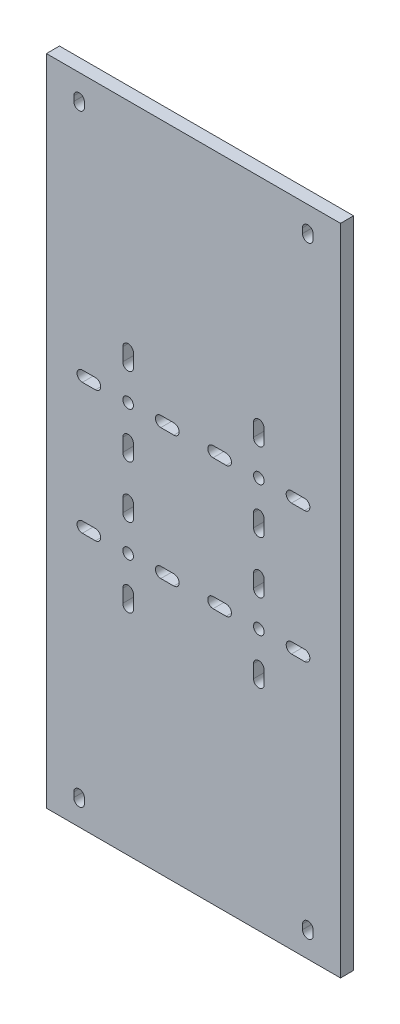
SolidWorks part; units mm, degrees
material "ABS PC"
ref_plane "前视基准面" through (0, 0, 0) normal (0, 0, 1) x (1, 0, 0)
ref_plane "上视基准面" through (0, 0, 0) normal (0, 1, 0) x (1, 0, 0)
ref_plane "右视基准面" through (0, 0, 0) normal (1, 0, 0) x (0, 0, -1)
sketch "草图1" plane through (0, 0, 0) normal (0, 0, 1) x (1, 0, 0)
  line L0 (-90, 369) -> (90, 369)
  line L1 (90, 369) -> (90, -15)
  line L2 (90, -15) -> (-90, -15)
  line L3 (-90, -15) -> (-90, 369)
  line L5 (-70, 360) -> (-70, 363) construction
  line L6 (-73.25, 360) -> (-73.25, 363)
  line L7 (-66.75, 360) -> (-66.75, 363)
  line L8 (0, 398.6227) -> (0, -66.7507) construction
  line L11 (-187.8062, 177) -> (345.6862, 177) construction
  line L12 (70, 360) -> (70, 363) construction
  line L13 (73.25, 360) -> (73.25, 363)
  line L14 (66.75, 360) -> (66.75, 363)
  line L15 (-70, -6) -> (-70, -9) construction
  line L16 (-73.25, -6) -> (-73.25, -9)
  line L17 (-66.75, -6) -> (-66.75, -9)
  line L18 (70, -6) -> (70, -9) construction
  line L19 (73.25, -6) -> (73.25, -9)
  line L20 (66.75, -6) -> (66.75, -9)
  line L21 (40, 217) -> (2, 217) construction
  line L22 (50, 207) -> (30, 207) construction
  line L23 (50, 207) -> (50, 227) construction
  line L24 (50, 227) -> (30, 227) construction
  line L25 (30, 207) -> (30, 227) construction
  line L26 (50, 207) -> (30, 227) construction
  line L27 (50, 227) -> (30, 207) construction
  line L28 (30, 227) -> (2, 227) construction
  line L29 (2, 227) -> (2, 207) construction
  line L30 (2, 207) -> (30, 207) construction
  line L31 (12, 217) -> (20, 217) construction
  line L32 (12, 220.25) -> (20, 220.25)
  line L33 (12, 213.75) -> (20, 213.75)
  line L34 (40, 245) -> (40, 237) construction
  line L37 (43.25, 245) -> (43.25, 237)
  line L40 (36.75, 245) -> (36.75, 237)
  line L43 (-40, 245) -> (-40, 237) construction
  line L46 (-43.25, 245) -> (-43.25, 237)
  line L49 (-36.75, 245) -> (-36.75, 237)
  line L52 (-12, 217) -> (-20, 217) construction
  line L55 (-12, 220.25) -> (-20, 220.25)
  line L58 (-12, 213.75) -> (-20, 213.75)
  line L61 (-40, 189) -> (-40, 197) construction
  line L64 (-36.75, 189) -> (-36.75, 197)
  line L67 (-43.25, 189) -> (-43.25, 197)
  line L70 (-68, 217) -> (-60, 217) construction
  line L73 (-68, 213.75) -> (-60, 213.75)
  line L76 (-68, 220.25) -> (-60, 220.25)
  line L79 (68, 217) -> (60, 217) construction
  line L80 (68, 213.75) -> (60, 213.75)
  line L81 (68, 220.25) -> (60, 220.25)
  line L82 (40, 189) -> (40, 197) construction
  line L83 (36.75, 189) -> (36.75, 197)
  line L84 (43.25, 189) -> (43.25, 197)
  line L85 (-68, 137) -> (-60, 137) construction
  line L86 (-68, 140.25) -> (-60, 140.25)
  line L87 (-68, 133.75) -> (-60, 133.75)
  line L88 (-40, 109) -> (-40, 117) construction
  line L89 (-43.25, 109) -> (-43.25, 117)
  line L90 (-36.75, 109) -> (-36.75, 117)
  line L91 (-12, 137) -> (-20, 137) construction
  line L92 (-12, 133.75) -> (-20, 133.75)
  line L93 (-12, 140.25) -> (-20, 140.25)
  line L94 (-40, 165) -> (-40, 157) construction
  line L95 (-36.75, 165) -> (-36.75, 157)
  line L96 (-43.25, 165) -> (-43.25, 157)
  line L97 (40, 109) -> (40, 117) construction
  line L98 (43.25, 109) -> (43.25, 117)
  line L99 (36.75, 109) -> (36.75, 117)
  line L100 (12, 137) -> (20, 137) construction
  line L101 (12, 133.75) -> (20, 133.75)
  line L102 (12, 140.25) -> (20, 140.25)
  line L103 (68, 137) -> (60, 137) construction
  line L104 (68, 140.25) -> (60, 140.25)
  line L105 (68, 133.75) -> (60, 133.75)
  line L106 (40, 165) -> (40, 157) construction
  line L107 (36.75, 165) -> (36.75, 157)
  line L108 (43.25, 165) -> (43.25, 157)
  arc A0 (-73.25, 360) -> (-66.75, 360) centre (-70, 360) ccw
  arc A1 (-66.75, 363) -> (-73.25, 363) centre (-70, 363) ccw
  arc A4 (73.25, 360) -> (66.75, 360) centre (70, 360) cw
  arc A5 (66.75, 363) -> (73.25, 363) centre (70, 363) cw
  arc A6 (-73.25, -6) -> (-66.75, -6) centre (-70, -6) cw
  arc A7 (-66.75, -9) -> (-73.25, -9) centre (-70, -9) cw
  arc A8 (73.25, -6) -> (66.75, -6) centre (70, -6) ccw
  arc A9 (66.75, -9) -> (73.25, -9) centre (70, -9) ccw
  circle A10 centre (40, 217) radius 3.25
  circle A11 centre (-40, 217) radius 3.25
  circle A12 centre (40, 137) radius 3.25
  circle A13 centre (-40, 137) radius 3.25
  arc A14 (12, 220.25) -> (12, 213.75) centre (12, 217) ccw
  arc A15 (20, 213.75) -> (20, 220.25) centre (20, 217) ccw
  arc A46 (43.25, 245) -> (36.75, 245) centre (40, 245) ccw
  arc A47 (36.75, 237) -> (43.25, 237) centre (40, 237) ccw
  arc A48 (68, 213.75) -> (68, 220.25) centre (68, 217) ccw
  arc A49 (60, 220.25) -> (60, 213.75) centre (60, 217) ccw
  arc A50 (36.75, 189) -> (43.25, 189) centre (40, 189) ccw
  arc A51 (43.25, 197) -> (36.75, 197) centre (40, 197) ccw
  arc A52 (-43.25, 245) -> (-36.75, 245) centre (-40, 245) cw
  arc A53 (-36.75, 237) -> (-43.25, 237) centre (-40, 237) cw
  arc A54 (-12, 220.25) -> (-12, 213.75) centre (-12, 217) cw
  arc A55 (-20, 213.75) -> (-20, 220.25) centre (-20, 217) cw
  arc A56 (-36.75, 189) -> (-43.25, 189) centre (-40, 189) cw
  arc A57 (-43.25, 197) -> (-36.75, 197) centre (-40, 197) cw
  arc A58 (-68, 213.75) -> (-68, 220.25) centre (-68, 217) cw
  arc A59 (-60, 220.25) -> (-60, 213.75) centre (-60, 217) cw
  arc A60 (-68, 140.25) -> (-68, 133.75) centre (-68, 137) ccw
  arc A61 (-60, 133.75) -> (-60, 140.25) centre (-60, 137) ccw
  arc A62 (-43.25, 109) -> (-36.75, 109) centre (-40, 109) ccw
  arc A63 (-36.75, 117) -> (-43.25, 117) centre (-40, 117) ccw
  arc A64 (-12, 133.75) -> (-12, 140.25) centre (-12, 137) ccw
  arc A65 (-20, 140.25) -> (-20, 133.75) centre (-20, 137) ccw
  arc A66 (-36.75, 165) -> (-43.25, 165) centre (-40, 165) ccw
  arc A67 (-43.25, 157) -> (-36.75, 157) centre (-40, 157) ccw
  arc A68 (43.25, 109) -> (36.75, 109) centre (40, 109) cw
  arc A69 (36.75, 117) -> (43.25, 117) centre (40, 117) cw
  arc A70 (12, 133.75) -> (12, 140.25) centre (12, 137) cw
  arc A71 (20, 140.25) -> (20, 133.75) centre (20, 137) cw
  arc A72 (68, 140.25) -> (68, 133.75) centre (68, 137) cw
  arc A73 (60, 133.75) -> (60, 140.25) centre (60, 137) cw
  arc A74 (36.75, 165) -> (43.25, 165) centre (40, 165) cw
  arc A75 (43.25, 157) -> (36.75, 157) centre (40, 157) cw
  point P12 (-70, 361.5)
  point P23 (70, 361.5)
  point P30 (-70, -7.5)
  point P37 (70, -7.5)
  point P57 (16, 217)
  point P66 (-40, 241)
  point P70 (40, 241)
  point P77 (64, 217)
  point P84 (40, 193)
  point P88 (40, 214.5)
  point P92 (-16, 217)
  point P99 (-40, 193)
  point P106 (-64, 217)
  point P113 (-64, 137)
  point P120 (-40, 113)
  point P127 (-16, 137)
  point P134 (-40, 161)
  point P141 (40, 113)
  point P148 (16, 137)
  point P155 (64, 137)
  point P162 (40, 161)
  point P173 (40, 217)
  dimension "D1" = 3.25
  dimension "D2" = 3
  dimension "D5" = 90
  dimension "D7" = 6.5
  dimension "D15" = 8
  dimension "D3" = 7.5
  dimension "D4" = 20
  dimension "D6" = 192
  dimension "D8" = 40
  dimension "D9" = 40
  dimension "D10" = 20
  dimension "D11" = 20
  dimension "D12" = 28
  dimension "D13" = 6.5
  dimension "D14" = 14
  dimension "D16" = 4
extrude "凸台-拉伸1" add sketch "草图1" along normal blind 8
sketch "草图2" plane through (0, 369, 0) normal (0, 1, 0) x (1, 0, 0)
  line L0 (-90, 0) -> (90, 0)
  line L1 (90, 0) -> (90, -8)
  line L2 (90, -8) -> (-90, -8)
  line L3 (-90, -8) -> (-90, 0)
extrude "凸台-拉伸2" add sketch "草图2" along normal blind 8
sketch "草图3" plane through (0, -15, 0) normal (0, -1, 0) x (1, 0, 0)
  line L0 (-90, 8) -> (90, 8)
  line L1 (90, 8) -> (90, 0)
  line L2 (90, 0) -> (-90, 0)
  line L3 (-90, 0) -> (-90, 8)
extrude "凸台-拉伸3" add sketch "草图3" along normal blind 8
